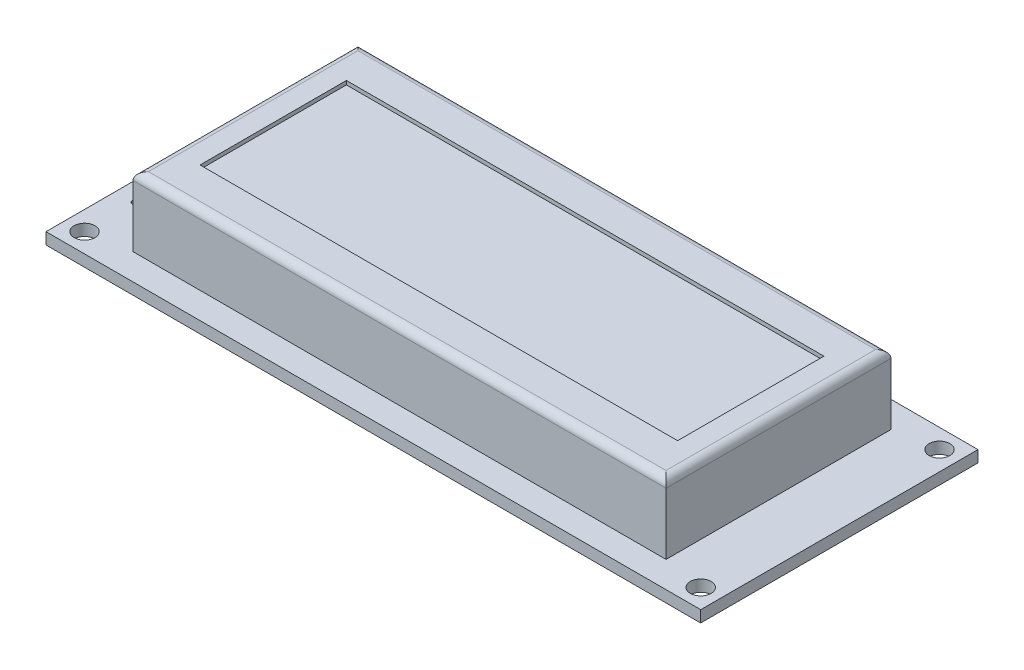
SolidWorks part; units mm, degrees
ref_plane "Спереди" through (0, 0, 0) normal (0, 0, 1) x (1, 0, 0)
ref_plane "Сверху" through (0, 0, 0) normal (0, 1, 0) x (1, 0, 0)
ref_plane "Справа" through (0, 0, 0) normal (1, 0, 0) x (0, 0, -1)
sketch "Эскиз1" plane through (0, 0, 0) normal (0, 1, 0) x (1, 0, 0)
  line L1 (-42.5, -18) -> (42.5, -18)
  line L2 (-42.5, -18) -> (-42.5, 18)
  line L3 (-42.5, 18) -> (42.5, 18)
  line L4 (42.5, -18) -> (42.5, 18)
  line L5 (-42.5, -18) -> (42.5, 18) construction
  line L6 (-42.5, 18) -> (42.5, -18) construction
  point P0 (0, 0)
  dimension "D1" = 85
  dimension "D2" = 36
extrude "Бобышка-Вытянуть1" add sketch "Эскиз1" along normal blind 1.5
sketch "Эскиз2" plane through (0, 1.5, 0) normal (0, 1, 0) x (1, 0, 0)
  line L1 (-34.6, -14.6) -> (34.6, -14.6)
  line L2 (-34.6, -14.6) -> (-34.6, 14.6)
  line L3 (-34.6, 14.6) -> (34.6, 14.6)
  line L4 (34.6, -14.6) -> (34.6, 14.6)
  line L5 (-34.6, -14.6) -> (34.6, 14.6) construction
  line L6 (-34.6, 14.6) -> (34.6, -14.6) construction
  point P0 (0, 0)
  dimension "D1" = 29.2
  dimension "D2" = 69.2
extrude "Бобышка-Вытянуть2" add sketch "Эскиз2" along normal blind 9
sketch "Эскиз3" plane through (0, 1.5, 0) normal (0, 1, 0) x (1, 0, 0)
  line L0 (0, 0) -> (0, 18) construction
  line L2 (0, 0) -> (-42.5, 0) construction
  line L3 (-42.5, 18) -> (-42.5, -18) construction
  circle A0 centre (-40, 15.5) radius 1.35
  circle A1 centre (-40, -15.5) radius 1.35
  circle A2 centre (40, -15.5) radius 1.35
  circle A3 centre (40, 15.5) radius 1.35
  dimension "D3" = 2.7
  dimension "D1" = 80
  dimension "D2" = 31
  dimension "D4" = 2.5
extrude "Вырез-Вытянуть1" cut sketch "Эскиз3" against normal up to next
sketch "Эскиз4" plane through (0, 10.5, 0) normal (0, 1, 0) x (1, 0, 0)
  line L1 (-31, -9.5) -> (31, -9.5)
  line L2 (-31, -9.5) -> (-31, 9.5)
  line L3 (-31, 9.5) -> (31, 9.5)
  line L4 (31, -9.5) -> (31, 9.5)
  line L5 (-31, -9.5) -> (31, 9.5) construction
  line L6 (-31, 9.5) -> (31, -9.5) construction
  point P0 (0, 0)
  dimension "D1" = 19
  dimension "D2" = 62
extrude "Вырез-Вытянуть2" cut sketch "Эскиз4" against normal blind 0.5
fillet "Скругление1" radius 1 4 edges at (0, 10.5, -14.6) (34.6, 10.5, 0) (0, 10.5, 14.6) (-34.6, 10.5, 0)
sketch "Эскиз5" plane through (0, 1.5, 0) normal (0, 1, 0) x (1, 0, 0)
  line L0 (0, 0) -> (-42.5, 0) construction
  line L1 (-42.5, 18) -> (-42.5, -18) construction
  circle A0 centre (-40, 8.89) radius 0.4
  dimension "D1" = 0.8
  dimension "D2" = 8.89
  dimension "D3" = 2.5
extrude "Вырез-Вытянуть3" cut sketch "Эскиз5" against normal up to next contours A0
pattern_linear "Линейный массив1" count 8 spacing 2.54 along (0, 0, 1) count 2 spacing 2.54 along (1, 0, 0) of "Вырез-Вытянуть3"
